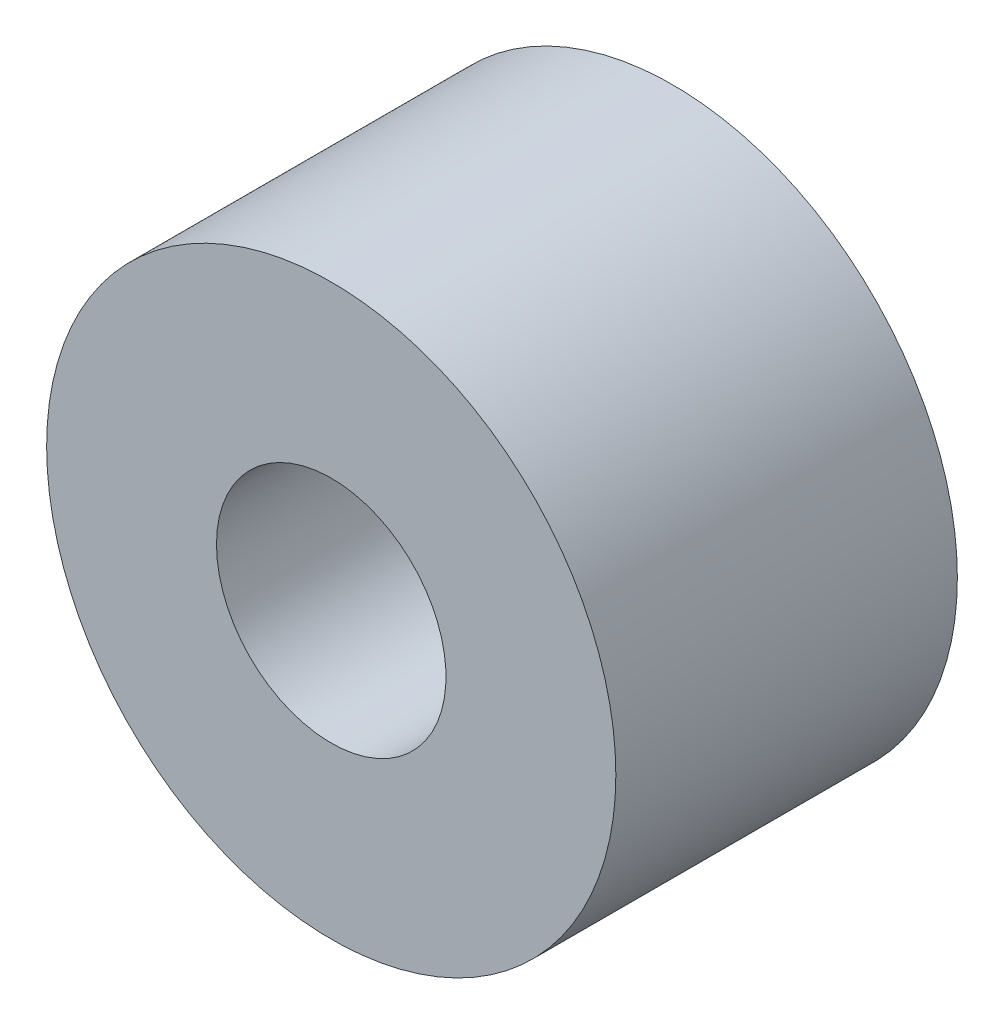
SolidWorks part; units mm, degrees
ref_plane "Front Plane" through (0, 0, 0) normal (0, 0, 1) x (1, 0, 0)
ref_plane "Top Plane" through (0, 0, 0) normal (0, 1, 0) x (1, 0, 0)
ref_plane "Right Plane" through (0, 0, 0) normal (1, 0, 0) x (0, 0, -1)
sketch "Sketch1" plane through (0, 0, 0) normal (0, 0, 1) x (1, 0, 0)
  circle A0 centre (0, 0) radius 7.9375
  circle A1 centre (0, 0) radius 3.2004
  dimension "OD" = 15.875
  dimension "ID" = 6.4008
extrude "Extrude1" add sketch "Sketch1" along normal mid plane 9.525
sketch "Sketch2" plane through (0, 0, 0) normal (1, 0, 0) x (0, 0, -1)
  line L0 (-4.7625, -3.2004) -> (4.7625, -3.2004) construction
  line L3 (4.7625, 3.2004) -> (-4.7625, 3.2004) construction
  line L5 (-4.7625, -3.2004) -> (4.7625, -3.2004)
  line L6 (4.7625, 3.2004) -> (-4.7625, 3.2004)
sketch "Sketch4" plane through (0, 0, 4.7625) normal (0, 0, 1) x (1, 0, 0)
  line L0 (0, 0) -> (-2.263, 2.263)
  line L1 (0, -2.1828) -> (0, 2.1828) construction
  circle A0 centre (0, 0) radius 3.2004 construction
  dimension "D1" = 45
